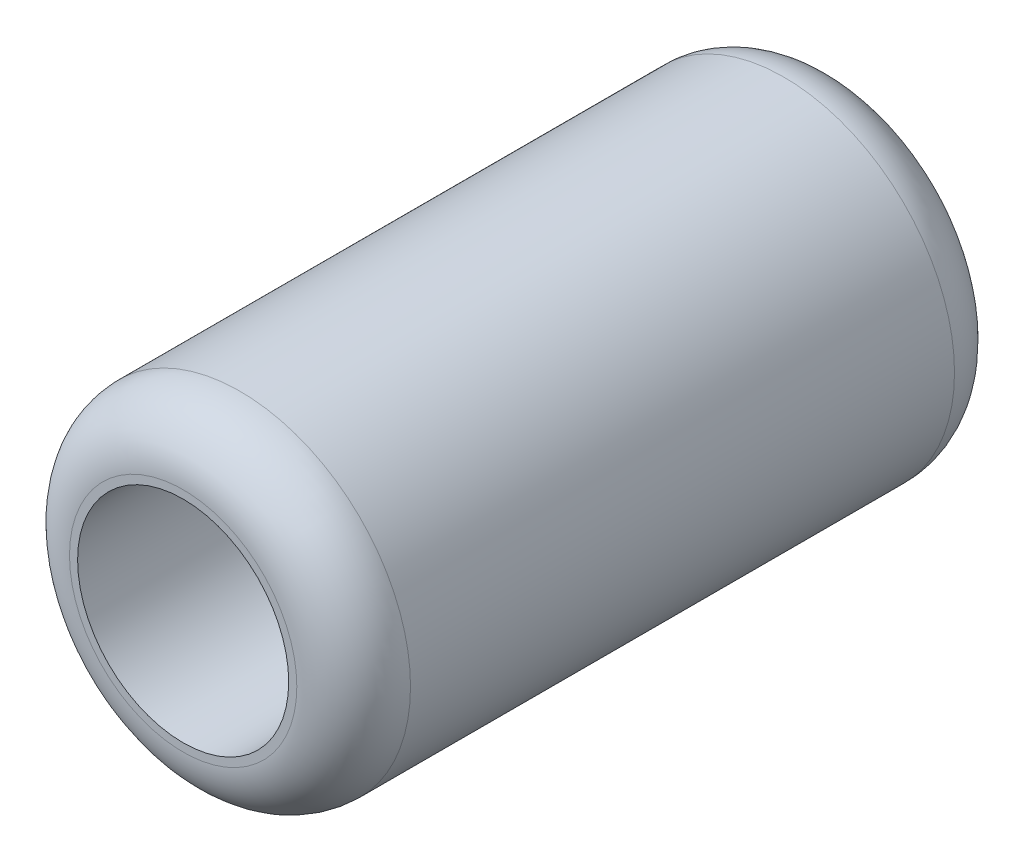
SolidWorks part; units mm, degrees
ref_plane "Front Plane" through (0, 0, 0) normal (0, 0, 1) x (1, 0, 0)
ref_plane "Top Plane" through (0, 0, 0) normal (0, 1, 0) x (1, 0, 0)
ref_plane "Right Plane" through (0, 0, 0) normal (1, 0, 0) x (0, 0, -1)
sketch "Sketch1" plane through (0, 0, 0) normal (0, 0, 1) x (1, 0, 0)
  circle A0 centre (0, 0) radius 10.5
extrude "Boss-Extrude1" add sketch "Sketch1" along normal blind 40.5
shell "Shell1" thickness 4
fillet "Fillet1" radius 3.5 1 edges at (10.5, 0, 40.5)
fillet "Fillet2" radius 3.5 1 edges at (10.5, 0, 0)
fillet "Fillet3" radius 1 1 edges at (6.5, 0, 4)
